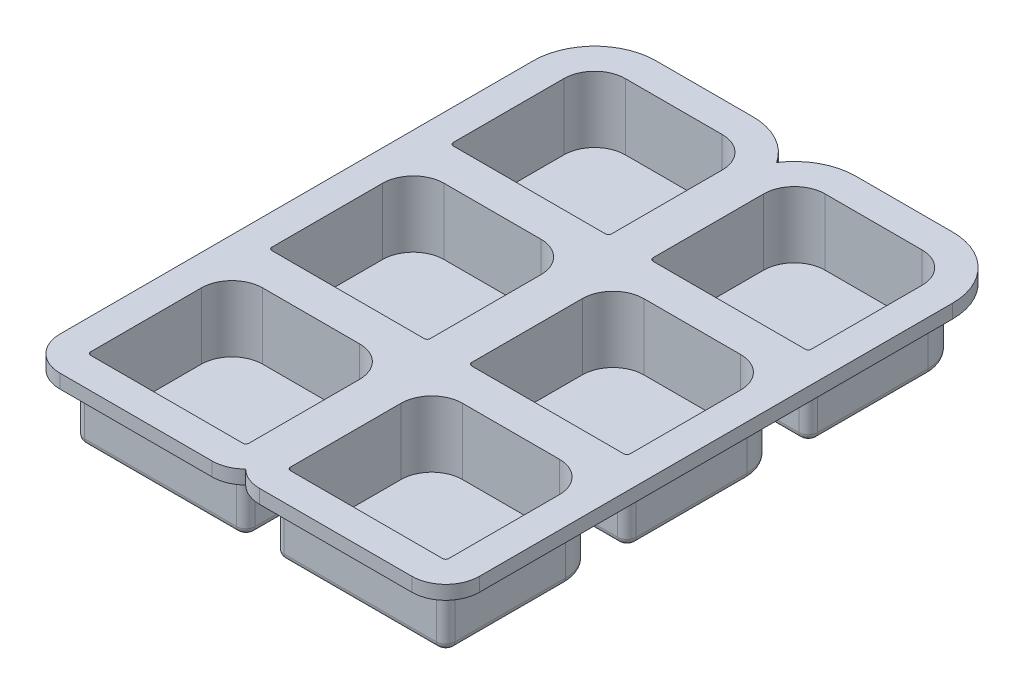
SolidWorks part; units mm, degrees
ref_plane "Alzado" through (0, 0, 0) normal (0, 0, 1) x (1, 0, 0)
ref_plane "Planta" through (0, 0, 0) normal (0, 1, 0) x (1, 0, 0)
ref_plane "Vista lateral" through (0, 0, 0) normal (1, 0, 0) x (0, 0, -1)
sketch "Croquis1" plane through (0, 0, 0) normal (0, 1, 0) x (1, 0, 0)
  line L0 (-48.265, 82.5) -> (-16.735, 82.5)
  line L1 (-6.735, 72.5) -> (-6.735, 36.5)
  line L2 (-7.735, 35.5) -> (-57.265, 35.5)
  line L3 (-58.265, 36.5) -> (-58.265, 72.5)
  line L4 (-32.5, 35.5) -> (-32.5, 82.5) construction
  line L5 (0, 97.5) -> (0, -97.5) construction
  line L6 (16.735, 82.5) -> (48.265, 82.5)
  line L7 (58.265, 72.5) -> (58.265, 36.5)
  line L8 (57.265, 35.5) -> (7.735, 35.5)
  line L9 (6.735, 36.5) -> (6.735, 72.5)
  line L10 (16.735, 23.5) -> (48.265, 23.5)
  line L11 (58.265, 13.5) -> (58.265, -22.5)
  line L12 (57.265, -23.5) -> (7.735, -23.5)
  line L13 (6.735, -22.5) -> (6.735, 13.5)
  line L14 (16.735, -35.5) -> (48.265, -35.5)
  line L15 (58.265, -45.5) -> (58.265, -81.5)
  line L16 (57.265, -82.5) -> (7.735, -82.5)
  line L17 (6.735, -81.5) -> (6.735, -45.5)
  line L18 (-48.265, 23.5) -> (-16.735, 23.5)
  line L19 (-6.735, 13.5) -> (-6.735, -22.5)
  line L20 (-7.735, -23.5) -> (-57.265, -23.5)
  line L21 (-58.265, -22.5) -> (-58.265, 13.5)
  line L22 (-48.265, -35.5) -> (-16.735, -35.5)
  line L23 (-6.735, -45.5) -> (-6.735, -81.5)
  line L24 (-7.735, -82.5) -> (-57.265, -82.5)
  line L25 (-58.265, -81.5) -> (-58.265, -45.5)
  line L26 (-48.265, 92.5) -> (-16.735, 92.5)
  line L29 (-68.265, 36.5) -> (-68.265, 72.5)
  line L32 (68.265, 72.5) -> (68.265, 36.5)
  line L33 (16.735, 92.5) -> (48.265, 92.5)
  line L34 (-68.265, -81.5) -> (-68.265, -45.5)
  line L37 (-7.735, -92.5) -> (-57.265, -92.5)
  line L40 (68.265, -45.5) -> (68.265, -81.5)
  line L41 (57.265, -92.5) -> (7.735, -92.5)
  line L42 (3.265, 72.5) -> (3.265, 36.5) construction
  line L43 (-3.265, 36.5) -> (-3.265, 72.5) construction
  line L44 (57.265, 25.5) -> (7.735, 25.5) construction
  line L45 (-7.735, 25.5) -> (-57.265, 25.5) construction
  line L46 (-48.265, -25.5) -> (-16.735, -25.5) construction
  line L47 (16.735, -25.5) -> (48.265, -25.5) construction
  line L48 (3.265, -45.5) -> (3.265, -81.5) construction
  line L49 (-3.265, -81.5) -> (-3.265, -45.5) construction
  line L50 (-68.265, 36.5) -> (-68.265, -45.5)
  line L51 (68.265, 36.5) -> (68.265, -45.5)
  arc A0 (-6.735, 72.5) -> (-16.735, 82.5) centre (-16.735, 72.5) ccw
  arc A1 (-7.735, 35.5) -> (-6.735, 36.5) centre (-7.735, 36.5) ccw
  arc A2 (-58.265, 36.5) -> (-57.265, 35.5) centre (-57.265, 36.5) ccw
  arc A3 (-48.265, 82.5) -> (-58.265, 72.5) centre (-48.265, 72.5) ccw
  arc A4 (58.265, 72.5) -> (48.265, 82.5) centre (48.265, 72.5) ccw
  arc A5 (57.265, 35.5) -> (58.265, 36.5) centre (57.265, 36.5) ccw
  arc A6 (6.735, 36.5) -> (7.735, 35.5) centre (7.735, 36.5) ccw
  arc A7 (16.735, 82.5) -> (6.735, 72.5) centre (16.735, 72.5) ccw
  arc A8 (58.265, 13.5) -> (48.265, 23.5) centre (48.265, 13.5) ccw
  arc A9 (57.265, -23.5) -> (58.265, -22.5) centre (57.265, -22.5) ccw
  arc A10 (6.735, -22.5) -> (7.735, -23.5) centre (7.735, -22.5) ccw
  arc A11 (16.735, 23.5) -> (6.735, 13.5) centre (16.735, 13.5) ccw
  arc A12 (58.265, -45.5) -> (48.265, -35.5) centre (48.265, -45.5) ccw
  arc A13 (57.265, -82.5) -> (58.265, -81.5) centre (57.265, -81.5) ccw
  arc A14 (6.735, -81.5) -> (7.735, -82.5) centre (7.735, -81.5) ccw
  arc A15 (16.735, -35.5) -> (6.735, -45.5) centre (16.735, -45.5) ccw
  arc A16 (-6.735, 13.5) -> (-16.735, 23.5) centre (-16.735, 13.5) ccw
  arc A17 (-7.735, -23.5) -> (-6.735, -22.5) centre (-7.735, -22.5) ccw
  arc A18 (-58.265, -22.5) -> (-57.265, -23.5) centre (-57.265, -22.5) ccw
  arc A19 (-48.265, 23.5) -> (-58.265, 13.5) centre (-48.265, 13.5) ccw
  arc A20 (-6.735, -45.5) -> (-16.735, -35.5) centre (-16.735, -45.5) ccw
  arc A21 (-7.735, -82.5) -> (-6.735, -81.5) centre (-7.735, -81.5) ccw
  arc A22 (-58.265, -81.5) -> (-57.265, -82.5) centre (-57.265, -81.5) ccw
  arc A23 (-48.265, -35.5) -> (-58.265, -45.5) centre (-48.265, -45.5) ccw
  arc A24 (0, 83.4517) -> (-16.735, 92.5) centre (-16.735, 72.5) ccw
  arc A27 (-48.265, 92.5) -> (-68.265, 72.5) centre (-48.265, 72.5) ccw
  arc A28 (16.735, 92.5) -> (0, 83.4517) centre (16.735, 72.5) ccw
  arc A31 (68.265, 72.5) -> (48.265, 92.5) centre (48.265, 72.5) ccw
  arc A34 (-7.735, -92.5) -> (0, -89.3211) centre (-7.735, -81.5) ccw
  arc A35 (-68.265, -81.5) -> (-57.265, -92.5) centre (-57.265, -81.5) ccw
  arc A38 (57.265, -92.5) -> (68.265, -81.5) centre (57.265, -81.5) ccw
  arc A40 (3.265, 72.5) -> (-16.735, 92.5) centre (-16.735, 72.5) ccw construction
  arc A41 (-3.265, 36.5) -> (7.735, 25.5) centre (7.735, 36.5) ccw construction
  arc A42 (-7.735, 25.5) -> (3.265, 36.5) centre (-7.735, 36.5) ccw construction
  arc A43 (16.735, 92.5) -> (-3.265, 72.5) centre (16.735, 72.5) ccw construction
  arc A44 (-68.265, 36.5) -> (-57.265, 25.5) centre (-57.265, 36.5) ccw construction
  arc A45 (57.265, 25.5) -> (68.265, 36.5) centre (57.265, 36.5) ccw construction
  arc A46 (-48.265, -25.5) -> (-68.265, -45.5) centre (-48.265, -45.5) ccw construction
  arc A47 (3.265, -45.5) -> (-16.735, -25.5) centre (-16.735, -45.5) ccw construction
  arc A48 (16.735, -25.5) -> (-3.265, -45.5) centre (16.735, -45.5) ccw construction
  arc A49 (68.265, -45.5) -> (48.265, -25.5) centre (48.265, -45.5) ccw construction
  arc A50 (-7.735, -92.5) -> (3.265, -81.5) centre (-7.735, -81.5) ccw construction
  arc A51 (-3.265, -81.5) -> (7.735, -92.5) centre (7.735, -81.5) ccw construction
  arc A52 (0, -89.3211) -> (7.735, -92.5) centre (7.735, -81.5) ccw
  point P15 (-58.265, 0)
  point P26 (0, 0)
  dimension "D2" = 10
  dimension "D4" = 1
  dimension "D1" = 31.53
  dimension "D3" = 36
  dimension "D5" = 49.53
  dimension "D6" = 2
  dimension "D8" = 195
  dimension "D9" = 165
  dimension "D10" = 82.5
  dimension "D11" = 32.5
  dimension "D12" = 10
  dimension "D7" = 3
extrude "Saliente-Extruir1" add sketch "Croquis1" along normal blind 21.5
sketch "Croquis2" plane through (0, 0, 0) normal (0, -1, 0) x (1, 0, 0)
  line L22 (60.265, -72.5) -> (60.265, -36.5)
  line L23 (16.735, -84.5) -> (48.265, -84.5)
  line L24 (4.735, -36.5) -> (4.735, -72.5)
  line L25 (57.265, -33.5) -> (7.735, -33.5)
  line L26 (60.265, -72.5) -> (60.265, -36.5)
  line L27 (16.735, -84.5) -> (48.265, -84.5)
  line L28 (4.735, -36.5) -> (4.735, -72.5)
  line L29 (57.265, -33.5) -> (7.735, -33.5)
  line L32 (-48.265, -92.5) -> (-16.735, -92.5)
  line L33 (16.735, -92.5) -> (48.265, -92.5)
  line L34 (68.265, -72.5) -> (68.265, 81.5)
  line L35 (-4.735, -72.5) -> (-4.735, -36.5)
  line L36 (-48.265, -84.5) -> (-16.735, -84.5)
  line L37 (-60.265, -36.5) -> (-60.265, -72.5)
  line L38 (-7.735, -33.5) -> (-57.265, -33.5)
  line L39 (-4.735, -72.5) -> (-4.735, -36.5)
  line L40 (-48.265, -84.5) -> (-16.735, -84.5)
  line L41 (-60.265, -36.5) -> (-60.265, -72.5)
  line L42 (-7.735, -33.5) -> (-57.265, -33.5)
  line L43 (57.265, 92.5) -> (7.735, 92.5)
  line L44 (-7.735, 92.5) -> (-57.265, 92.5)
  line L45 (-68.265, 81.5) -> (-68.265, -72.5)
  line L46 (-48.265, -92.5) -> (-16.735, -92.5)
  line L47 (16.735, -92.5) -> (48.265, -92.5)
  line L48 (-48.265, 33.5) -> (-16.735, 33.5)
  line L49 (-4.735, 45.5) -> (-4.735, 81.5)
  line L50 (-60.265, 81.5) -> (-60.265, 45.5)
  line L51 (-7.735, 84.5) -> (-57.265, 84.5)
  line L52 (-48.265, 33.5) -> (-16.735, 33.5)
  line L53 (-4.735, 45.5) -> (-4.735, 81.5)
  line L54 (-60.265, 81.5) -> (-60.265, 45.5)
  line L55 (-7.735, 84.5) -> (-57.265, 84.5)
  line L56 (68.265, -72.5) -> (68.265, 81.5)
  line L57 (57.265, 92.5) -> (7.735, 92.5)
  line L58 (-7.735, 92.5) -> (-57.265, 92.5)
  line L59 (-68.265, 81.5) -> (-68.265, -72.5)
  line L75 (16.735, 33.5) -> (48.265, 33.5)
  line L76 (60.265, 45.5) -> (60.265, 81.5)
  line L77 (57.265, 84.5) -> (7.735, 84.5)
  line L78 (4.735, 81.5) -> (4.735, 45.5)
  line L79 (16.735, 33.5) -> (48.265, 33.5)
  line L80 (60.265, 45.5) -> (60.265, 81.5)
  line L81 (57.265, 84.5) -> (7.735, 84.5)
  line L82 (4.735, 81.5) -> (4.735, 45.5)
  line L99 (-7.735, 25.5) -> (-57.265, 25.5)
  line L100 (-4.735, -13.5) -> (-4.735, 22.5)
  line L101 (-48.265, -25.5) -> (-16.735, -25.5)
  line L102 (-60.265, 22.5) -> (-60.265, -13.5)
  line L103 (-7.735, 25.5) -> (-57.265, 25.5)
  line L104 (-4.735, -13.5) -> (-4.735, 22.5)
  line L105 (-48.265, -25.5) -> (-16.735, -25.5)
  line L106 (-60.265, 22.5) -> (-60.265, -13.5)
  line L123 (57.265, 25.5) -> (7.735, 25.5)
  line L124 (60.265, -13.5) -> (60.265, 22.5)
  line L125 (16.735, -25.5) -> (48.265, -25.5)
  line L126 (4.735, 22.5) -> (4.735, -13.5)
  line L127 (57.265, 25.5) -> (7.735, 25.5)
  line L128 (60.265, -13.5) -> (60.265, 22.5)
  line L129 (16.735, -25.5) -> (48.265, -25.5)
  line L130 (4.735, 22.5) -> (4.735, -13.5)
  arc A19 (48.265, -84.5) -> (60.265, -72.5) centre (48.265, -72.5) ccw
  arc A20 (60.265, -36.5) -> (57.265, -33.5) centre (57.265, -36.5) ccw
  arc A21 (4.735, -72.5) -> (16.735, -84.5) centre (16.735, -72.5) ccw
  arc A22 (7.735, -33.5) -> (4.735, -36.5) centre (7.735, -36.5) ccw
  arc A23 (48.265, -84.5) -> (60.265, -72.5) centre (48.265, -72.5) ccw
  arc A24 (60.265, -36.5) -> (57.265, -33.5) centre (57.265, -36.5) ccw
  arc A25 (4.735, -72.5) -> (16.735, -84.5) centre (16.735, -72.5) ccw
  arc A26 (7.735, -33.5) -> (4.735, -36.5) centre (7.735, -36.5) ccw
  arc A31 (-68.265, -72.5) -> (-48.265, -92.5) centre (-48.265, -72.5) ccw
  arc A32 (-16.735, -92.5) -> (0, -83.4517) centre (-16.735, -72.5) ccw
  arc A33 (0, -83.4517) -> (16.735, -92.5) centre (16.735, -72.5) ccw
  arc A34 (48.265, -92.5) -> (68.265, -72.5) centre (48.265, -72.5) ccw
  arc A35 (-4.735, -36.5) -> (-7.735, -33.5) centre (-7.735, -36.5) ccw
  arc A36 (-16.735, -84.5) -> (-4.735, -72.5) centre (-16.735, -72.5) ccw
  arc A37 (-60.265, -72.5) -> (-48.265, -84.5) centre (-48.265, -72.5) ccw
  arc A38 (-57.265, -33.5) -> (-60.265, -36.5) centre (-57.265, -36.5) ccw
  arc A39 (-4.735, -36.5) -> (-7.735, -33.5) centre (-7.735, -36.5) ccw
  arc A40 (-16.735, -84.5) -> (-4.735, -72.5) centre (-16.735, -72.5) ccw
  arc A41 (-60.265, -72.5) -> (-48.265, -84.5) centre (-48.265, -72.5) ccw
  arc A42 (-57.265, -33.5) -> (-60.265, -36.5) centre (-57.265, -36.5) ccw
  arc A43 (68.265, 81.5) -> (57.265, 92.5) centre (57.265, 81.5) ccw
  arc A44 (-60.265, 45.5) -> (-48.265, 33.5) centre (-48.265, 45.5) ccw
  arc A45 (-16.735, 33.5) -> (-4.735, 45.5) centre (-16.735, 45.5) ccw
  arc A46 (-4.735, 81.5) -> (-7.735, 84.5) centre (-7.735, 81.5) ccw
  arc A47 (-57.265, 84.5) -> (-60.265, 81.5) centre (-57.265, 81.5) ccw
  arc A48 (-60.265, 45.5) -> (-48.265, 33.5) centre (-48.265, 45.5) ccw
  arc A49 (-16.735, 33.5) -> (-4.735, 45.5) centre (-16.735, 45.5) ccw
  arc A50 (-4.735, 81.5) -> (-7.735, 84.5) centre (-7.735, 81.5) ccw
  arc A51 (-57.265, 84.5) -> (-60.265, 81.5) centre (-57.265, 81.5) ccw
  arc A52 (7.735, 92.5) -> (0, 89.3211) centre (7.735, 81.5) ccw
  arc A53 (0, 89.3211) -> (-7.735, 92.5) centre (-7.735, 81.5) ccw
  arc A54 (-57.265, 92.5) -> (-68.265, 81.5) centre (-57.265, 81.5) ccw
  arc A55 (-68.265, -72.5) -> (-48.265, -92.5) centre (-48.265, -72.5) ccw
  arc A56 (-16.735, -92.5) -> (0, -83.4517) centre (-16.735, -72.5) ccw
  arc A57 (0, -83.4517) -> (16.735, -92.5) centre (16.735, -72.5) ccw
  arc A58 (48.265, -92.5) -> (68.265, -72.5) centre (48.265, -72.5) ccw
  arc A59 (68.265, 81.5) -> (57.265, 92.5) centre (57.265, 81.5) ccw
  arc A60 (7.735, 92.5) -> (0, 89.3211) centre (7.735, 81.5) ccw
  arc A61 (0, 89.3211) -> (-7.735, 92.5) centre (-7.735, 81.5) ccw
  arc A62 (-57.265, 92.5) -> (-68.265, 81.5) centre (-57.265, 81.5) ccw
  arc A69 (48.265, 33.5) -> (60.265, 45.5) centre (48.265, 45.5) ccw
  arc A70 (4.735, 45.5) -> (16.735, 33.5) centre (16.735, 45.5) ccw
  arc A71 (60.265, 81.5) -> (57.265, 84.5) centre (57.265, 81.5) ccw
  arc A72 (7.735, 84.5) -> (4.735, 81.5) centre (7.735, 81.5) ccw
  arc A73 (48.265, 33.5) -> (60.265, 45.5) centre (48.265, 45.5) ccw
  arc A74 (4.735, 45.5) -> (16.735, 33.5) centre (16.735, 45.5) ccw
  arc A75 (60.265, 81.5) -> (57.265, 84.5) centre (57.265, 81.5) ccw
  arc A76 (7.735, 84.5) -> (4.735, 81.5) centre (7.735, 81.5) ccw
  arc A97 (-4.735, 22.5) -> (-7.735, 25.5) centre (-7.735, 22.5) ccw
  arc A98 (-16.735, -25.5) -> (-4.735, -13.5) centre (-16.735, -13.5) ccw
  arc A99 (-60.265, -13.5) -> (-48.265, -25.5) centre (-48.265, -13.5) ccw
  arc A100 (-57.265, 25.5) -> (-60.265, 22.5) centre (-57.265, 22.5) ccw
  arc A101 (-4.735, 22.5) -> (-7.735, 25.5) centre (-7.735, 22.5) ccw
  arc A102 (-16.735, -25.5) -> (-4.735, -13.5) centre (-16.735, -13.5) ccw
  arc A103 (-60.265, -13.5) -> (-48.265, -25.5) centre (-48.265, -13.5) ccw
  arc A104 (-57.265, 25.5) -> (-60.265, 22.5) centre (-57.265, 22.5) ccw
  arc A125 (60.265, 22.5) -> (57.265, 25.5) centre (57.265, 22.5) ccw
  arc A126 (48.265, -25.5) -> (60.265, -13.5) centre (48.265, -13.5) ccw
  arc A127 (4.735, -13.5) -> (16.735, -25.5) centre (16.735, -13.5) ccw
  arc A128 (7.735, 25.5) -> (4.735, 22.5) centre (7.735, 22.5) ccw
  arc A129 (60.265, 22.5) -> (57.265, 25.5) centre (57.265, 22.5) ccw
  arc A130 (48.265, -25.5) -> (60.265, -13.5) centre (48.265, -13.5) ccw
  arc A131 (4.735, -13.5) -> (16.735, -25.5) centre (16.735, -13.5) ccw
  arc A132 (7.735, 25.5) -> (4.735, 22.5) centre (7.735, 22.5) ccw
  dimension "D1" = 2
  dimension "D2" = 2
  dimension "D3" = 2
  dimension "D4" = 2
  dimension "D5" = 2
  dimension "D6" = 2
  dimension "D7" = 0
extrude "Cortar-Extruir1" cut sketch "Croquis2" against normal blind 17
sketch "Croquis3" plane through (0, 0, 0) normal (0, -1, 0) x (1, 0, 0)
  line L4 (60.265, 45.5) -> (60.265, 81.5)
  line L5 (57.265, 84.5) -> (7.735, 84.5)
  line L6 (4.735, 81.5) -> (4.735, 45.5)
  line L7 (16.735, 33.5) -> (48.265, 33.5)
  line L8 (60.265, 45.5) -> (60.265, 81.5)
  line L9 (57.265, 84.5) -> (7.735, 84.5)
  line L10 (4.735, 81.5) -> (4.735, 45.5)
  line L11 (16.735, 33.5) -> (48.265, 33.5)
  line L12 (-48.265, 33.5) -> (-16.735, 33.5)
  line L13 (-4.735, 45.5) -> (-4.735, 81.5)
  line L14 (-7.735, 84.5) -> (-57.265, 84.5)
  line L15 (-60.265, 81.5) -> (-60.265, 45.5)
  line L16 (-48.265, 33.5) -> (-16.735, 33.5)
  line L17 (-4.735, 45.5) -> (-4.735, 81.5)
  line L18 (-7.735, 84.5) -> (-57.265, 84.5)
  line L19 (-60.265, 81.5) -> (-60.265, 45.5)
  line L20 (-7.735, 25.5) -> (-57.265, 25.5)
  line L21 (-60.265, 22.5) -> (-60.265, -13.5)
  line L22 (-48.265, -25.5) -> (-16.735, -25.5)
  line L23 (-4.735, -13.5) -> (-4.735, 22.5)
  line L24 (-7.735, 25.5) -> (-57.265, 25.5)
  line L25 (-60.265, 22.5) -> (-60.265, -13.5)
  line L26 (-48.265, -25.5) -> (-16.735, -25.5)
  line L27 (-4.735, -13.5) -> (-4.735, 22.5)
  line L28 (57.265, 25.5) -> (7.735, 25.5)
  line L29 (4.735, 22.5) -> (4.735, -13.5)
  line L30 (16.735, -25.5) -> (48.265, -25.5)
  line L31 (60.265, -13.5) -> (60.265, 22.5)
  line L32 (57.265, 25.5) -> (7.735, 25.5)
  line L33 (4.735, 22.5) -> (4.735, -13.5)
  line L34 (16.735, -25.5) -> (48.265, -25.5)
  line L35 (60.265, -13.5) -> (60.265, 22.5)
  line L36 (-7.735, -33.5) -> (-57.265, -33.5)
  line L37 (-60.265, -36.5) -> (-60.265, -72.5)
  line L38 (-48.265, -84.5) -> (-16.735, -84.5)
  line L39 (-4.735, -72.5) -> (-4.735, -36.5)
  line L40 (-7.735, -33.5) -> (-57.265, -33.5)
  line L41 (-60.265, -36.5) -> (-60.265, -72.5)
  line L42 (-48.265, -84.5) -> (-16.735, -84.5)
  line L43 (-4.735, -72.5) -> (-4.735, -36.5)
  line L44 (60.265, -72.5) -> (60.265, -36.5)
  line L45 (57.265, -33.5) -> (7.735, -33.5)
  line L46 (4.735, -36.5) -> (4.735, -72.5)
  line L47 (16.735, -84.5) -> (48.265, -84.5)
  line L48 (60.265, -72.5) -> (60.265, -36.5)
  line L49 (57.265, -33.5) -> (7.735, -33.5)
  line L50 (4.735, -36.5) -> (4.735, -72.5)
  line L51 (16.735, -84.5) -> (48.265, -84.5)
  arc A4 (48.265, 33.5) -> (60.265, 45.5) centre (48.265, 45.5) ccw
  arc A5 (60.265, 81.5) -> (57.265, 84.5) centre (57.265, 81.5) ccw
  arc A6 (7.735, 84.5) -> (4.735, 81.5) centre (7.735, 81.5) ccw
  arc A7 (4.735, 45.5) -> (16.735, 33.5) centre (16.735, 45.5) ccw
  arc A8 (48.265, 33.5) -> (60.265, 45.5) centre (48.265, 45.5) ccw
  arc A9 (60.265, 81.5) -> (57.265, 84.5) centre (57.265, 81.5) ccw
  arc A10 (7.735, 84.5) -> (4.735, 81.5) centre (7.735, 81.5) ccw
  arc A11 (4.735, 45.5) -> (16.735, 33.5) centre (16.735, 45.5) ccw
  arc A12 (-60.265, 45.5) -> (-48.265, 33.5) centre (-48.265, 45.5) ccw
  arc A13 (-16.735, 33.5) -> (-4.735, 45.5) centre (-16.735, 45.5) ccw
  arc A14 (-4.735, 81.5) -> (-7.735, 84.5) centre (-7.735, 81.5) ccw
  arc A15 (-57.265, 84.5) -> (-60.265, 81.5) centre (-57.265, 81.5) ccw
  arc A16 (-60.265, 45.5) -> (-48.265, 33.5) centre (-48.265, 45.5) ccw
  arc A17 (-16.735, 33.5) -> (-4.735, 45.5) centre (-16.735, 45.5) ccw
  arc A18 (-4.735, 81.5) -> (-7.735, 84.5) centre (-7.735, 81.5) ccw
  arc A19 (-57.265, 84.5) -> (-60.265, 81.5) centre (-57.265, 81.5) ccw
  arc A20 (-4.735, 22.5) -> (-7.735, 25.5) centre (-7.735, 22.5) ccw
  arc A21 (-57.265, 25.5) -> (-60.265, 22.5) centre (-57.265, 22.5) ccw
  arc A22 (-60.265, -13.5) -> (-48.265, -25.5) centre (-48.265, -13.5) ccw
  arc A23 (-16.735, -25.5) -> (-4.735, -13.5) centre (-16.735, -13.5) ccw
  arc A24 (-4.735, 22.5) -> (-7.735, 25.5) centre (-7.735, 22.5) ccw
  arc A25 (-57.265, 25.5) -> (-60.265, 22.5) centre (-57.265, 22.5) ccw
  arc A26 (-60.265, -13.5) -> (-48.265, -25.5) centre (-48.265, -13.5) ccw
  arc A27 (-16.735, -25.5) -> (-4.735, -13.5) centre (-16.735, -13.5) ccw
  arc A28 (60.265, 22.5) -> (57.265, 25.5) centre (57.265, 22.5) ccw
  arc A29 (7.735, 25.5) -> (4.735, 22.5) centre (7.735, 22.5) ccw
  arc A30 (4.735, -13.5) -> (16.735, -25.5) centre (16.735, -13.5) ccw
  arc A31 (48.265, -25.5) -> (60.265, -13.5) centre (48.265, -13.5) ccw
  arc A32 (60.265, 22.5) -> (57.265, 25.5) centre (57.265, 22.5) ccw
  arc A33 (7.735, 25.5) -> (4.735, 22.5) centre (7.735, 22.5) ccw
  arc A34 (4.735, -13.5) -> (16.735, -25.5) centre (16.735, -13.5) ccw
  arc A35 (48.265, -25.5) -> (60.265, -13.5) centre (48.265, -13.5) ccw
  arc A36 (-4.735, -36.5) -> (-7.735, -33.5) centre (-7.735, -36.5) ccw
  arc A37 (-57.265, -33.5) -> (-60.265, -36.5) centre (-57.265, -36.5) ccw
  arc A38 (-60.265, -72.5) -> (-48.265, -84.5) centre (-48.265, -72.5) ccw
  arc A39 (-16.735, -84.5) -> (-4.735, -72.5) centre (-16.735, -72.5) ccw
  arc A40 (-4.735, -36.5) -> (-7.735, -33.5) centre (-7.735, -36.5) ccw
  arc A41 (-57.265, -33.5) -> (-60.265, -36.5) centre (-57.265, -36.5) ccw
  arc A42 (-60.265, -72.5) -> (-48.265, -84.5) centre (-48.265, -72.5) ccw
  arc A43 (-16.735, -84.5) -> (-4.735, -72.5) centre (-16.735, -72.5) ccw
  arc A44 (48.265, -84.5) -> (60.265, -72.5) centre (48.265, -72.5) ccw
  arc A45 (60.265, -36.5) -> (57.265, -33.5) centre (57.265, -36.5) ccw
  arc A46 (7.735, -33.5) -> (4.735, -36.5) centre (7.735, -36.5) ccw
  arc A47 (4.735, -72.5) -> (16.735, -84.5) centre (16.735, -72.5) ccw
  arc A48 (48.265, -84.5) -> (60.265, -72.5) centre (48.265, -72.5) ccw
  arc A49 (60.265, -36.5) -> (57.265, -33.5) centre (57.265, -36.5) ccw
  arc A50 (7.735, -33.5) -> (4.735, -36.5) centre (7.735, -36.5) ccw
  arc A51 (4.735, -72.5) -> (16.735, -84.5) centre (16.735, -72.5) ccw
  dimension "D1" = 0
  dimension "D2" = 0
  dimension "D3" = 0
  dimension "D4" = 0
  dimension "D5" = 0
  dimension "D6" = 0
extrude "Saliente-Extruir2" add sketch "Croquis3" along normal blind 3
fillet "Redondeo2" radius 2 96 edges at (-56.7503, -3, 37.0147) (-60.265, -3, 63.5) (-59.3863, -3, 83.6213) (-32.5, -3, 84.5) (-5.6137, -3, 83.6213) (-4.735, -3, 63.5) (-8.2497, -3, 37.0147) (8.2497, -3, 37.0147) (4.735, -3, 63.5) (5.6137, -3, 83.6213) (32.5, -3, 84.5) (59.3863, -3, 83.6213) (60.265, -3, 63.5) (56.7503, -3, 37.0147) (-56.7503, -3, -21.9853) (-60.265, -3, 4.5) (-59.3863, -3, 24.6213) (-32.5, -3, 25.5) (-5.6137, -3, 24.6213) (-4.735, -3, 4.5) (-8.2497, -3, -21.9853) (8.2497, -3, -21.9853) (4.735, -3, 4.5) (5.6137, -3, 24.6213) (32.5, -3, 25.5) (59.3863, -3, 24.6213) (60.265, -3, 4.5) (56.7503, -3, -21.9853) (-56.7503, -3, -80.9853) (-60.265, -3, -54.5) (-59.3863, -3, -34.3787) (-32.5, -3, -33.5) (-5.6137, -3, -34.3787) (-4.735, -3, -54.5) (-8.2497, -3, -80.9853) (8.2497, -3, -80.9853) (4.735, -3, -54.5) (5.6137, -3, -34.3787) (32.5, -3, -33.5) (59.3863, -3, -34.3787) (60.265, -3, -54.5) (56.7503, -3, -80.9853) (-32.5, -3, 33.5) (32.5, -3, 33.5) (-32.5, -3, -25.5) (32.5, -3, -25.5) (-32.5, -3, -84.5) (32.5, -3, -84.5) (5.6137, 17, 83.6213) (32.5, 17, 84.5) (59.3863, 17, 83.6213) (60.265, 17, 63.5) (56.7503, 17, 37.0147) (32.5, 17, 33.5) (8.2497, 17, 37.0147) (5.6137, 17, 24.6213) (32.5, 17, 25.5) (59.3863, 17, 24.6213) (60.265, 17, 4.5) (56.7503, 17, -21.9853) (32.5, 17, -25.5) (8.2497, 17, -21.9853) (-59.3863, 17, 83.6213) (-32.5, 17, 84.5) (-5.6137, 17, 83.6213) (-4.735, 17, 63.5) (-8.2497, 17, 37.0147) (-32.5, 17, 33.5) (-56.7503, 17, 37.0147) (-59.3863, 17, 24.6213) (-32.5, 17, 25.5) (-5.6137, 17, 24.6213) (-4.735, 17, 4.5) (-8.2497, 17, -21.9853) (-32.5, 17, -25.5) (-56.7503, 17, -21.9853) (8.2497, 17, -80.9853) (4.735, 17, -54.5) (5.6137, 17, -34.3787) (32.5, 17, -33.5) (59.3863, 17, -34.3787) (60.265, 17, -54.5) (56.7503, 17, -80.9853) (-59.3863, 17, -34.3787) (-32.5, 17, -33.5) (-5.6137, 17, -34.3787) (-4.735, 17, -54.5) (-8.2497, 17, -80.9853) (-32.5, 17, -84.5) (-56.7503, 17, -80.9853) (4.735, 17, 63.5) (4.735, 17, 4.5) (-60.265, 17, 63.5) (-60.265, 17, 4.5) (32.5, 17, -84.5) (-60.265, 17, -54.5)
